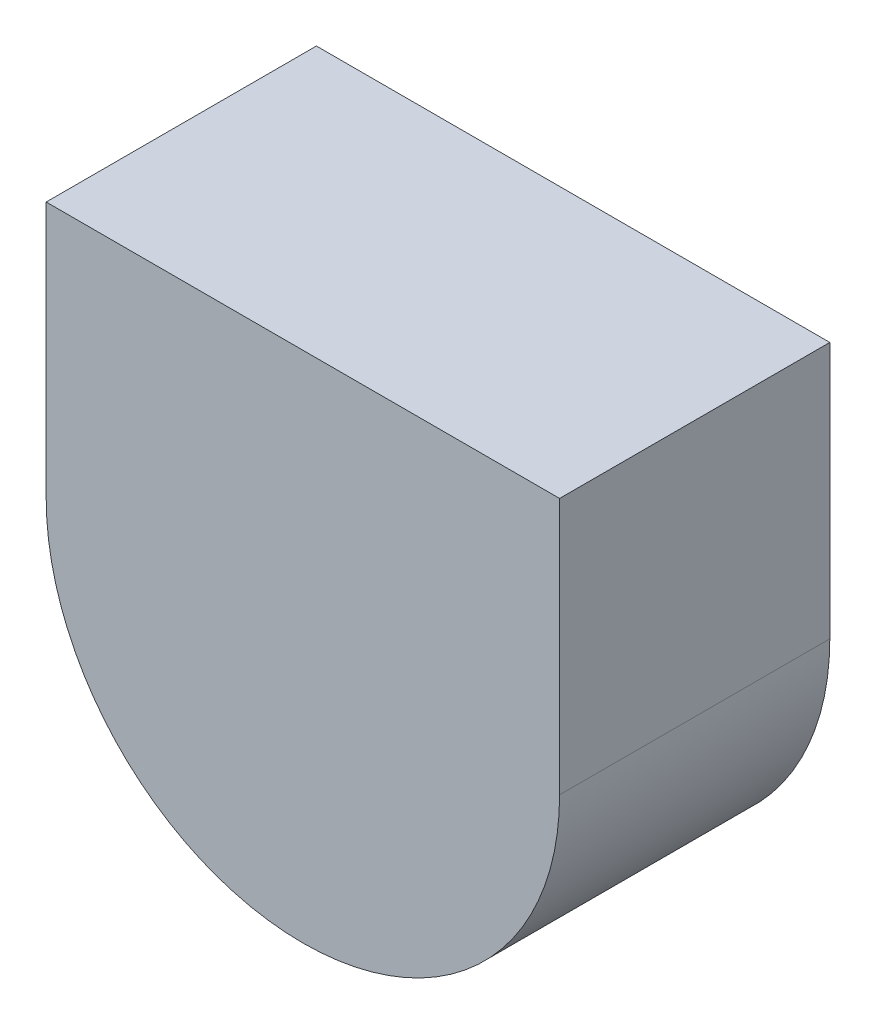
SolidWorks part; units mm, degrees
ref_plane "Front Plane" through (0, 0, 0) normal (0, 0, 1) x (1, 0, 0)
ref_plane "Top Plane" through (0, 0, 0) normal (0, 1, 0) x (1, 0, 0)
ref_plane "Right Plane" through (0, 0, 0) normal (1, 0, 0) x (0, 0, -1)
sketch "Sketch1" plane through (0, 0, 0) normal (0, 0, 1) x (1, 0, 0)
  line L2 (-19, 0) -> (-19, 19)
  line L3 (-19, 19) -> (19, 19)
  line L4 (19, 0) -> (19, 19)
  line L5 (-13.435, -13.435) -> (19, 19) construction
  line L6 (-19, 19) -> (13.435, -13.435) construction
  arc A0 (-19, 0) -> (19, 0) centre (0, 0) ccw
  point P0 (0, 0)
  point P4 (20, 20)
  point P8 (0, 0)
  dimension "D2" = 19
  dimension "D1" = 38
extrude "Boss-Extrude1" add sketch "Sketch1" along normal blind 20 contours L2 L3 L4 A0
